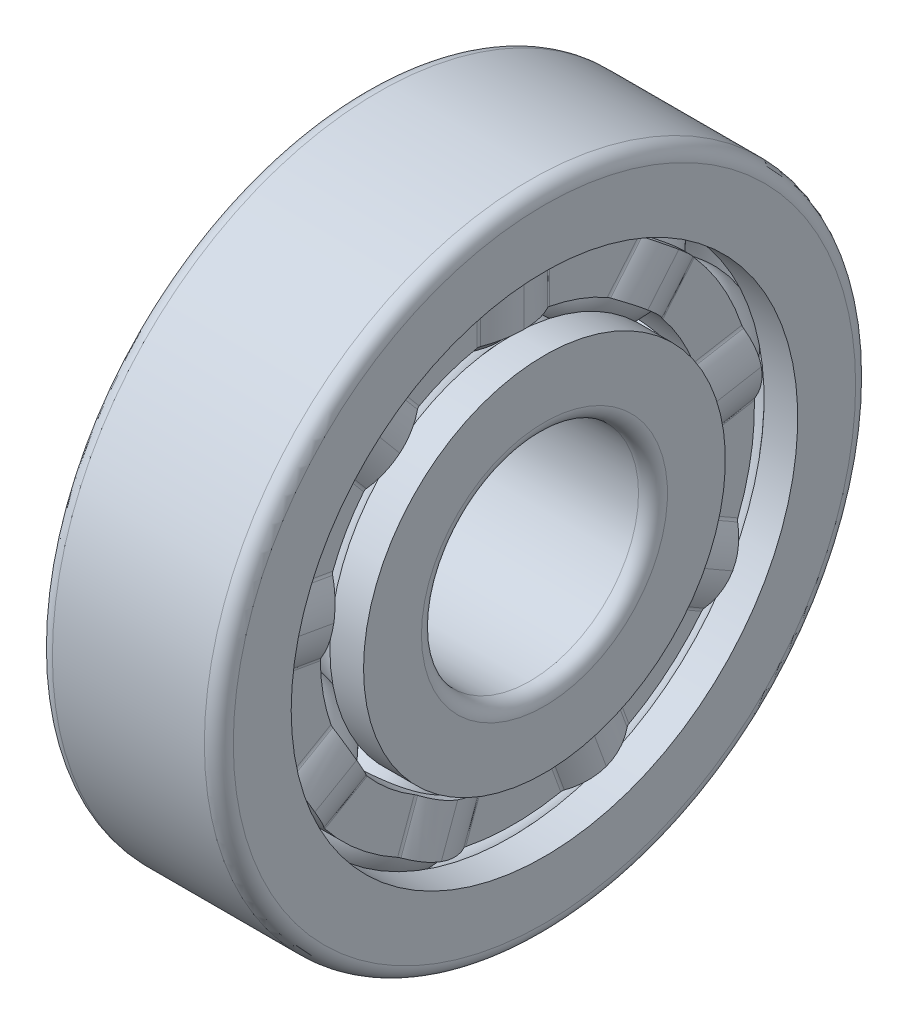
SolidWorks part; units mm, degrees
ref_plane "Front" through (0, 0, 0) normal (0, 0, 1) x (1, 0, 0)
ref_plane "Top" through (0, 0, 0) normal (0, 1, 0) x (1, 0, 0)
ref_plane "Right" through (0, 0, 0) normal (1, 0, 0) x (0, 0, -1)
sketch "Support-Front-Body" plane through (0, 0, 0) normal (0, 0, 1) x (1, 0, 0)
  line L0 (-1.25, 0) -> (1.25, 0) construction
  line L1 (1.25, 0) -> (1.25, 1.5) construction
  line L2 (-1.25, 0) -> (-1.25, 1.5) construction
  line L4 (-1.25, 4.5) -> (1.25, 4.5)
  line L5 (-1.25, 4.5) -> (-1.25, 3.5)
  line L6 (-1.25, 3.5) -> (1.25, 3.5)
  line L7 (1.25, 4.5) -> (1.25, 3.5)
  line L8 (-1.25, 2.5) -> (1.25, 2.5)
  line L9 (-1.25, 2.5) -> (-1.25, 1.5)
  line L10 (-1.25, 1.5) -> (1.25, 1.5)
  line L11 (1.25, 2.5) -> (1.25, 1.5)
  line L13 (-1.25, 3) -> (1.25, 3) construction
  line L14 (0, 0) -> (0, 1.5) construction
  line L15 (0, 1.5) -> (0, 2.5) construction
  line L16 (0, 2.5) -> (0, 3.5) construction
  line L17 (0, 3.5) -> (0, 4.5) construction
  dimension "Diam-Inner" = 3
  dimension "Diam-Outer" = 9
  dimension "CC-Ball" = 6
  dimension "Width-Inner" = 2.5
sketch "Support-Front-Ball" plane through (0, 0, 0) normal (0, 0, 1) x (1, 0, 0)
  line L0 (-0.9, 3) -> (0.9, 3) construction
  line L1 (0, 0) -> (0, 2.1) construction
  line L2 (-1.25, 3) -> (1.25, 3) construction
  line L3 (0, 3) -> (0, 3.9) construction
  line L6 (0, 2.1) -> (0, 3) construction
  circle A0 centre (0, 3) radius 0.9
  dimension "Diam-Ball" = 1.8
sketch "Support-Front-Groove" plane through (0, 0, 0) normal (0, 0, 1) x (1, 0, 0)
  line L0 (0, 3.5) -> (0, 3.3333) construction
  line L1 (0, 3.3333) -> (0, 3.1667) construction
  line L2 (0, 3.1667) -> (0, 3) construction
  line L3 (-1.25, 3) -> (1.25, 3) construction
  line L4 (-0.9, 3) -> (0.9, 3) construction
  line L6 (-1.25, 3.5) -> (1.25, 3.5) construction
  line L7 (0, 2.1367) -> (0, 2.1) construction
  line L8 (0.7483, 2.5) -> (0.7851, 2.5) construction
  line L9 (-1.25, 2.5) -> (1.25, 2.5) construction
  line L11 (0, 0) -> (0, 2.1) construction
  line L12 (-0.9, 3) -> (0.9, 3) construction
  circle A0 centre (0, 3) radius 0.9 construction
  circle A1 centre (0, 3.1667) radius 1.0299
  circle A2 centre (0, 2.8333) radius 1.0299
sketch "Support-Front-Ball-Cage" plane through (0, 0, 0) normal (0, 0, 1) x (1, 0, 0)
  line L0 (0.9, 3) -> (-0.9644, 3) construction
  line L1 (-0.9644, 3.3333) -> (0.9644, 3.3333)
  line L2 (-0.9644, 3.3333) -> (-0.9644, 2.6667)
  line L3 (-0.9644, 2.6667) -> (0.9644, 2.6667)
  line L4 (0.9644, 3.3333) -> (0.9644, 2.6667)
  line L5 (-1.25, 3) -> (1.25, 3) construction
  line L6 (0, 2.6667) -> (0, 3.3333) construction
  line L7 (0, 2.5) -> (0, 3.5) construction
  line L8 (0.9, 3) -> (0.9644, 3) construction
  line L9 (0.9322, 3) -> (0.9322, 3.1667) construction
  line L10 (0.9322, 3.1667) -> (0.9322, 3.3333) construction
  line L11 (0.9322, 3.3333) -> (0.9322, 3.5) construction
  line L12 (-1.25, 3.5) -> (1.25, 3.5) construction
  line L13 (0.9644, 3.4167) -> (0.7977, 3.4167) construction
  line L14 (0, 3.3333) -> (0, 3.9644) construction
  circle A0 centre (0, 3) radius 0.9 construction
  circle A1 centre (0, 3) radius 0.9644 construction
  point P26 (0.9322, 3.4167)
sketch "Support-Right-Ball-Cage" plane through (0, 0, 0) normal (1, 0, 0) x (0, 0, -1)
  line L0 (0, 0) -> (0, 4.5) construction
  line L1 (0, 0) -> (-2.8925, 3.4472) construction
  line L2 (0, 2.0356) -> (-1.3085, 1.5594) construction
  line L3 (-2.5483, 3.0369) -> (0, 3.9644) construction
  line L4 (0, 0) -> (-1.6308, 4.1941) construction
  line L6 (-1.4466, 4.2611) -> (0, 0) construction
  circle A0 centre (0, 0) radius 2.6667
  circle A1 centre (0, 0) radius 3.3333
  circle A2 centre (0, 3) radius 0.9644
  circle A3 centre (0, 0) radius 3 construction
  circle A4 centre (-1.9284, 2.2981) radius 0.9644
  dimension "Angle-Ball" = 40
ref_plane "Ref-Plane-1" through (0, 1.7975, 0.6542) normal (0, 0.9397, 0.342) x (-1, 0, 0)
sketch "Support-Ball-Gage-Inner" plane through (0, 1.7975, 0.6542) normal (0, 0.9397, 0.342) x (-1, 0, 0)
  line L0 (-0.8184, -0.1632) -> (-0.8184, 0.1632)
  line L1 (0.8184, -0.1632) -> (0.8184, 0.1632)
  line L2 (0.9644, 0.6962) -> (0.9644, -0.6962)
  line L3 (-0.9644, 0) -> (-0.8184, 0) construction
  line L4 (-0.9, -1.0261) -> (-0.9, -0.1632) construction
  line L5 (-0.9, -0.1632) -> (-0.8184, -0.1632) construction
  line L6 (-0.9, -0.1632) -> (-0.9, -0.0816) construction
  line L7 (-0.9, -0.0816) -> (-0.9, 0) construction
  line L8 (-0.8184, 0) -> (0, 0) construction
  line L9 (-0.9644, 0.6962) -> (-0.9644, -0.6962)
  line L10 (-0.9644, -1.1401) -> (-0.9644, -0.9121) construction
  line L11 (-0.9, -0.0816) -> (-0.8184, -0.1632) construction
  line L12 (0, 0.6962) -> (0, -0.6962) construction
  arc A0 (-0.9644, -0.6962) -> (-0.8298, -0.2048) centre (0, -0.6962) cw
  arc A1 (-0.8298, -0.2048) -> (-0.8184, -0.1632) centre (-0.9, -0.1632) ccw
  arc A2 (-0.8184, 0.1632) -> (-0.8298, 0.2048) centre (-0.9, 0.1632) ccw
  arc A3 (-0.8298, 0.2048) -> (-0.9644, 0.6962) centre (0, 0.6962) cw
  arc A4 (0.8298, 0.2048) -> (0.9644, 0.6962) centre (0, 0.6962) ccw
  arc A5 (0.8184, 0.1632) -> (0.8298, 0.2048) centre (0.9, 0.1632) cw
  arc A6 (0.8298, -0.2048) -> (0.8184, -0.1632) centre (0.9, -0.1632) cw
  arc A7 (0.9644, -0.6962) -> (0.8298, -0.2048) centre (0, -0.6962) ccw
  dimension "D1" = 45
ref_plane "Ref-Plane-2" through (0, 3.5007, 1.2741) normal (0, -0.9397, -0.342) x (1, 0, 0)
sketch "Support-Ball-Gage-Outer" plane through (0, 3.5007, 1.2741) normal (0, -0.9397, -0.342) x (1, 0, 0)
  line L0 (0.9644, 1.3559) -> (0.9644, -1.3559)
  line L1 (0.8184, -0.8229) -> (0.8184, 0.8229)
  line L2 (0.9644, 0.6962) -> (0.9644, -0.6962) construction
  line L7 (0.8184, -0.1632) -> (0.8184, 0.1632) construction
  line L8 (0, 1.3559) -> (0, -1.3559) construction
  line L9 (-0.9644, 1.3559) -> (-0.9644, -1.3559)
  line L10 (-0.8184, -0.8229) -> (-0.8184, 0.8229)
  arc A0 (0.9644, -1.3559) -> (0.8298, -0.8645) centre (0, -1.3559) ccw
  arc A1 (0.8298, -0.8645) -> (0.8184, -0.8229) centre (0.9, -0.8229) cw
  arc A2 (0.8184, 0.8229) -> (0.8298, 0.8645) centre (0.9, 0.8229) cw
  arc A3 (0.8298, 0.8645) -> (0.9644, 1.3559) centre (0, 1.3559) ccw
  arc A4 (0.8298, 0.2048) -> (0.8184, 0.1632) centre (0.9, 0.1632) ccw construction
  arc A5 (-0.8298, -0.8645) -> (-0.8184, -0.8229) centre (-0.9, -0.8229) ccw
  arc A6 (-0.9644, -1.3559) -> (-0.8298, -0.8645) centre (0, -1.3559) cw
  arc A7 (-0.8298, 0.8645) -> (-0.9644, 1.3559) centre (0, 1.3559) cw
  arc A8 (-0.8184, 0.8229) -> (-0.8298, 0.8645) centre (-0.9, 0.8229) ccw
ref_axis "Ref-Axis" through (-2.75, 0, 0) along (1, 0, 0)
ref_plane "Ref-Plane-Right" through (1.25, 0, 0) normal (1, 0, 0) x (0, 0, -1)
ref_plane "Ref-Plane-Left" through (-1.25, 0, 0) normal (1, 0, 0) x (0, 0, -1)
sketch "Sketch7" plane through (0, 0, 0) normal (0, 0, 1) x (1, 0, 0)
  line L0 (-0.9, 3) -> (0.9, 3) construction
  line L2 (-0.9, 3) -> (0.9, 3) construction
  line L4 (-0.9, 3) -> (0.9, 3)
  circle A0 centre (0, 3) radius 0.9 construction
  arc A1 (-0.9, 3) -> (0.9, 3) centre (0, 3) ccw
revolve "Body-Ball" add sketch "Sketch7" angle 360 about L2
sketch "Sketch10" plane through (0, 0, 0) normal (0, 0, 1) x (1, 0, 0)
  line L0 (-1.25, 0) -> (1.25, 0) construction
  line L1 (-0.9644, 3.3333) -> (-0.9644, 2.6667) construction
  line L2 (-0.9644, 3.3333) -> (0.9644, 3.3333) construction
  line L3 (0.9644, 3.3333) -> (0.9644, 2.6667) construction
  line L4 (-0.9644, 2.6667) -> (0.9644, 2.6667) construction
  line L5 (-1.25, 0) -> (1.25, 0) construction
  line L6 (-0.9644, 3.3333) -> (-0.9644, 2.6667)
  line L7 (-0.9644, 3.3333) -> (0.9644, 3.3333)
  line L8 (0.9644, 3.3333) -> (0.9644, 2.6667)
  line L9 (-0.9644, 2.6667) -> (0.9644, 2.6667)
revolve "Body-Ball-Cage" add sketch "Sketch10" angle 360 about L5
sketch "Sketch16" plane through (0, 1.7975, 0.6542) normal (0, 0.9397, 0.342) x (-1, 0, 0)
  line L0 (0.8184, -0.1632) -> (0.8184, 0.1632) construction
  line L1 (0.9644, 0.6962) -> (0.9644, -0.6962) construction
  line L2 (0.8184, -0.1632) -> (0.8184, 0.1632)
  line L3 (0.9644, 0.6962) -> (0.9644, -0.6962)
  arc A0 (0.8298, 0.2048) -> (0.9644, 0.6962) centre (0, 0.6962) ccw construction
  arc A1 (0.8298, 0.2048) -> (0.8184, 0.1632) centre (0.9, 0.1632) ccw construction
  arc A2 (0.8184, -0.1632) -> (0.8298, -0.2048) centre (0.9, -0.1632) ccw construction
  arc A3 (0.9644, -0.6962) -> (0.8298, -0.2048) centre (0, -0.6962) ccw construction
  arc A4 (0.8298, 0.2048) -> (0.9644, 0.6962) centre (0, 0.6962) ccw
  arc A5 (0.8298, 0.2048) -> (0.8184, 0.1632) centre (0.9, 0.1632) ccw
  arc A6 (0.8184, -0.1632) -> (0.8298, -0.2048) centre (0.9, -0.1632) ccw
  arc A7 (0.9644, -0.6962) -> (0.8298, -0.2048) centre (0, -0.6962) ccw
sketch "Sketch17" plane through (0, 3.5007, 1.2741) normal (0, -0.9397, -0.342) x (1, 0, 0)
  line L0 (-0.8184, -0.8229) -> (-0.8184, 0.8229) construction
  line L1 (-0.9644, 1.3559) -> (-0.9644, -1.3559) construction
  line L2 (-0.8184, -0.8229) -> (-0.8184, 0.8229)
  line L3 (-0.9644, 1.3559) -> (-0.9644, -1.3559)
  arc A0 (-0.9644, 1.3559) -> (-0.8298, 0.8645) centre (0, 1.3559) ccw construction
  arc A1 (-0.8184, 0.8229) -> (-0.8298, 0.8645) centre (-0.9, 0.8229) ccw construction
  arc A2 (-0.8298, -0.8645) -> (-0.8184, -0.8229) centre (-0.9, -0.8229) ccw construction
  arc A3 (-0.8298, -0.8645) -> (-0.9644, -1.3559) centre (0, -1.3559) ccw construction
  arc A4 (-0.9644, 1.3559) -> (-0.8298, 0.8645) centre (0, 1.3559) ccw
  arc A5 (-0.8184, 0.8229) -> (-0.8298, 0.8645) centre (-0.9, 0.8229) ccw
  arc A6 (-0.8298, -0.8645) -> (-0.8184, -0.8229) centre (-0.9, -0.8229) ccw
  arc A7 (-0.8298, -0.8645) -> (-0.9644, -1.3559) centre (0, -1.3559) ccw
loft "Cut-Ball-Cage-1" cut profiles "Sketch16", "Sketch17"
sketch "Sketch14" plane through (0, 1.7975, 0.6542) normal (0, 0.9397, 0.342) x (-1, 0, 0)
  line L0 (-0.8184, -0.1632) -> (-0.8184, 0.1632) construction
  line L1 (-0.9644, 0.6962) -> (-0.9644, -0.6962) construction
  line L2 (-0.8184, -0.1632) -> (-0.8184, 0.1632)
  line L3 (-0.9644, 0.6962) -> (-0.9644, -0.6962)
  arc A0 (-0.9644, 0.6962) -> (-0.8298, 0.2048) centre (0, 0.6962) ccw construction
  arc A1 (-0.8184, 0.1632) -> (-0.8298, 0.2048) centre (-0.9, 0.1632) ccw construction
  arc A2 (-0.8298, -0.2048) -> (-0.8184, -0.1632) centre (-0.9, -0.1632) ccw construction
  arc A3 (-0.8298, -0.2048) -> (-0.9644, -0.6962) centre (0, -0.6962) ccw construction
  arc A4 (-0.9644, 0.6962) -> (-0.8298, 0.2048) centre (0, 0.6962) ccw
  arc A5 (-0.8184, 0.1632) -> (-0.8298, 0.2048) centre (-0.9, 0.1632) ccw
  arc A6 (-0.8298, -0.2048) -> (-0.8184, -0.1632) centre (-0.9, -0.1632) ccw
  arc A7 (-0.8298, -0.2048) -> (-0.9644, -0.6962) centre (0, -0.6962) ccw
sketch "Sketch15" plane through (0, 3.5007, 1.2741) normal (0, -0.9397, -0.342) x (1, 0, 0)
  line L0 (0.8184, -0.8229) -> (0.8184, 0.8229) construction
  line L1 (0.9644, 1.3559) -> (0.9644, -1.3559) construction
  line L2 (0.8184, -0.8229) -> (0.8184, 0.8229)
  line L3 (0.9644, 1.3559) -> (0.9644, -1.3559)
  arc A0 (0.8298, 0.8645) -> (0.9644, 1.3559) centre (0, 1.3559) ccw construction
  arc A1 (0.8298, 0.8645) -> (0.8184, 0.8229) centre (0.9, 0.8229) ccw construction
  arc A2 (0.8184, -0.8229) -> (0.8298, -0.8645) centre (0.9, -0.8229) ccw construction
  arc A3 (0.9644, -1.3559) -> (0.8298, -0.8645) centre (0, -1.3559) ccw construction
  arc A4 (0.8298, 0.8645) -> (0.9644, 1.3559) centre (0, 1.3559) ccw
  arc A5 (0.8298, 0.8645) -> (0.8184, 0.8229) centre (0.9, 0.8229) ccw
  arc A6 (0.8184, -0.8229) -> (0.8298, -0.8645) centre (0.9, -0.8229) ccw
  arc A7 (0.9644, -1.3559) -> (0.8298, -0.8645) centre (0, -1.3559) ccw
loft "Cut-Ball-Cage-2" cut profiles "Sketch15", "Sketch14"
pattern_circular "Pattern-Ball" count 9 over 360 about axis through (-2.75, 0, 0) along (1, 0, 0) of "Body-Ball", "Cut-Ball-Cage-2", "Cut-Ball-Cage-1"
sketch "Sketch2" plane through (0, 0, 0) normal (0, 0, 1) x (1, 0, 0)
  line L4 (-1.25, 2.5) -> (-1.25, 1.5) construction
  line L5 (-1.25, 2.5) -> (1.25, 2.5) construction
  line L6 (1.25, 2.5) -> (1.25, 1.5) construction
  line L7 (-1.25, 1.5) -> (1.25, 1.5) construction
  line L8 (-1.25, 0) -> (1.25, 0) construction
  line L9 (-1.25, 0) -> (1.25, 0) construction
  line L10 (-1.25, 2.5) -> (-1.25, 1.5)
  line L11 (-1.25, 2.5) -> (-0.7851, 2.5)
  line L12 (1.25, 2.5) -> (1.25, 1.5)
  line L13 (-1.25, 1.5) -> (1.25, 1.5)
  line L14 (0.7851, 2.5) -> (1.25, 2.5)
  circle A1 centre (0, 3.1667) radius 1.0299 construction
  arc A2 (-0.7851, 2.5) -> (0.7851, 2.5) centre (0, 3.1667) ccw
sketch "Sketch8" plane through (0, 0, 0) normal (0, 0, 1) x (1, 0, 0)
  line L0 (-1.25, 0) -> (1.25, 0) construction
  line L1 (-1.25, 4.5) -> (-1.25, 3.5) construction
  line L2 (-1.25, 3.5) -> (1.25, 3.5) construction
  line L3 (1.25, 4.5) -> (1.25, 3.5) construction
  line L4 (-1.25, 0) -> (1.25, 0) construction
  line L9 (-1.25, 4.5) -> (1.25, 4.5) construction
  line L10 (-1.25, 4.5) -> (-1.25, 3.5)
  line L11 (-1.25, 3.5) -> (-0.7851, 3.5)
  line L12 (1.25, 4.5) -> (1.25, 3.5)
  line L13 (-1.25, 4.5) -> (1.25, 4.5)
  line L14 (0.7851, 3.5) -> (1.25, 3.5)
  circle A1 centre (0, 2.8333) radius 1.0299 construction
  arc A2 (0.7851, 3.5) -> (-0.7851, 3.5) centre (0, 2.8333) ccw
revolve "Body-Inner" add sketch "Sketch2" angle 360 about L9
revolve "Body-Outer" add sketch "Sketch8" angle 360 about L4
fillet "Cosmetic-Fillet-Outer-1" radius 0.2 1 edges at (-1.25, 0, 4.5)
fillet "Cosmetic-Fillet-Outer-2" radius 0.2 1 edges at (1.25, 0, 4.5)
fillet "Cosmetic-Fillet-Inner-1" radius 0.2 1 edges at (-1.25, 0, 1.5)
fillet "Cosmetic-Fillet-Inner-2" radius 0.2 1 edges at (1.25, 0, 1.5)
equation "\"Diam-Ball@Support-Front-Ball\"=(((\"Diam-Outer@Support-Front-Body\"-\"Diam-Inner@Support-Front-Body\")/2)*3)/5"
equation "\"Num-Ball@Pattern-Ball\"=INT((PI*(\"Diam-Outer@Support-Front-Body\"-((\"Diam-Outer@Support-Front-Body\"-\"Diam-Inner@Support-Front-Body\")/2)))/(\"Diam-Ball@Support-Front-Ball\"*1.2))"
equation "\"Angle-Ball@Support-Right-Ball-Cage\" = 360 / INT(((PI*(\"Diam-Outer@Support-Front-Body\"-((\"Diam-Outer@Support-Front-Body\"-\"Diam-Inner@Support-Front-Body\")/4)))/2)/\"Diam-Ball@Support-Front-Ball\")"
equation "\"Angle-Ball@Support-Right-Ball-Cage\" = 360 / \"Num-Ball@Pattern-Ball\""
